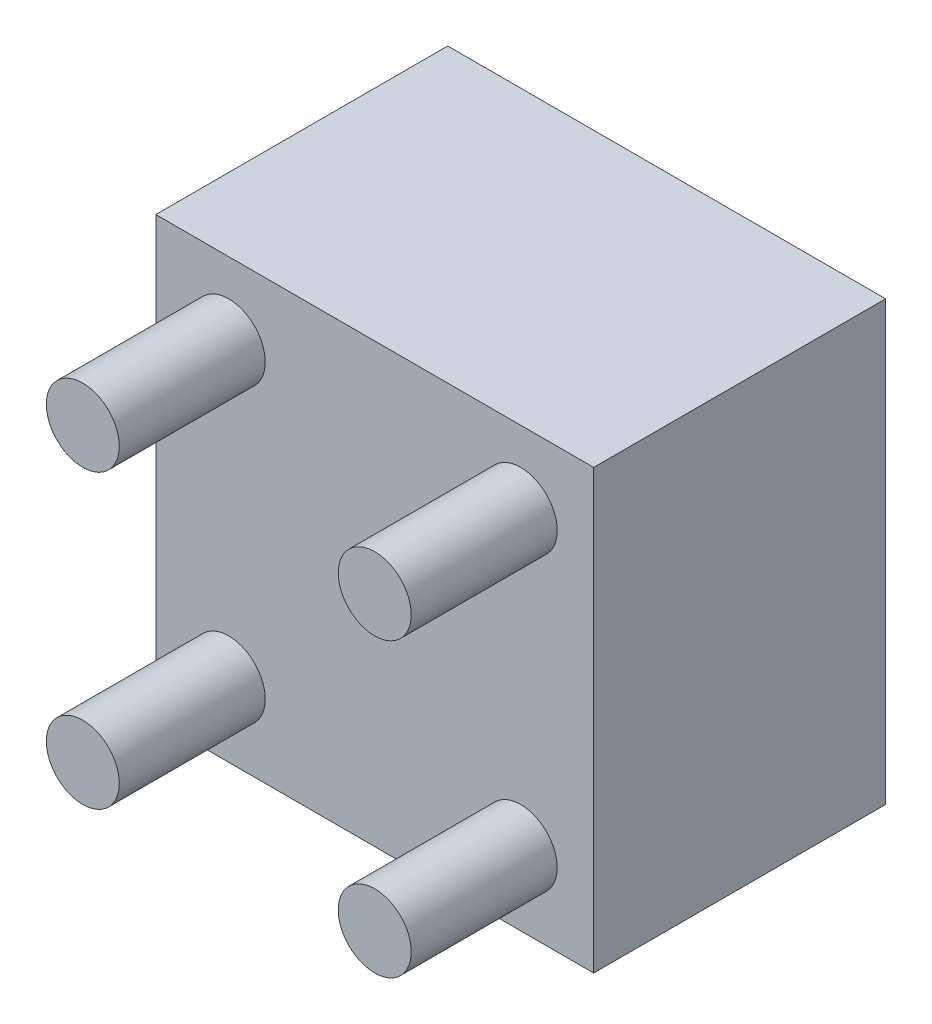
SolidWorks part; units mm, degrees
ref_plane "Front Plane" through (0, 0, 0) normal (0, 0, 1) x (1, 0, 0)
ref_plane "Top Plane" through (0, 0, 0) normal (0, 1, 0) x (1, 0, 0)
ref_plane "Right Plane" through (0, 0, 0) normal (1, 0, 0) x (0, 0, -1)
sketch "Sketch1" plane through (0, 0, 0) normal (0, 0, 1) x (1, 0, 0)
  line L1 (-30.8145, 18.5973) -> (29.1855, 18.5973)
  line L2 (-30.8145, 18.5973) -> (-30.8145, -41.4027)
  line L3 (-30.8145, -41.4027) -> (29.1855, -41.4027)
  line L4 (29.1855, 18.5973) -> (29.1855, -41.4027)
  dimension "D1" = 60
  dimension "D2" = 60
extrude "Boss-Extrude1" add sketch "Sketch1" along normal blind 40
sketch "Sketch6" plane through (0, 0, 40) normal (0, 0, 1) x (1, 0, 0)
  line L0 (-30.8145, 18.5973) -> (-20.8145, 18.5973)
  line L1 (29.1855, 18.5973) -> (-30.8145, 18.5973) construction
  line L2 (-20.8145, 18.5973) -> (-20.8145, 8.5973)
  line L3 (-0.8145, 18.5973) -> (-0.8145, 45.5299)
  circle A0 centre (-20.8145, 8.5973) radius 5
  circle A1 centre (19.1855, 8.5973) radius 5
  circle A2 centre (19.1855, -31.4027) radius 5
  circle A3 centre (-20.8145, -31.4027) radius 5
  dimension "D1" = 10
  dimension "D2" = 10
extrude "Boss-Extrude3" add sketch "Sketch6" along normal blind 20
